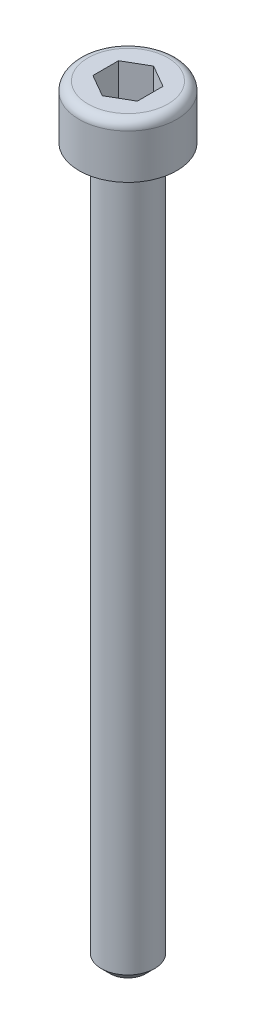
SolidWorks part; units mm, degrees
material "acero"
ref_plane "Alzado" through (0, 0, 0) normal (0, 0, 1) x (1, 0, 0)
ref_plane "Planta" through (0, 0, 0) normal (0, 1, 0) x (1, 0, 0)
ref_plane "Vista lateral" through (0, 0, 0) normal (1, 0, 0) x (0, 0, -1)
sketch "Croquis1" plane through (0, 0, 0) normal (0, 0, 1) x (1, 0, 0)
  line L0 (0, 0) -> (0, -60.9498) construction
  line L1 (0, 0) -> (2.75, 0)
  line L2 (2.75, 0) -> (2.75, -3)
  line L3 (2.75, -3) -> (1.5, -3)
  line L4 (1.5, -3) -> (1.5, -43)
  line L5 (1.5, -43) -> (0, -43)
  line L6 (0, -43) -> (0, 0)
  dimension "D1" = 40
  dimension "D2" = 3
  dimension "D3" = 5.5
  dimension "D4" = 3
revolve "Revolución1" add sketch "Croquis1" angle 360 about L0
sketch "Croquis2" plane through (0, 0, 0) normal (0, 1, 0) x (1, 0, 0)
  line L1 (1.25, 0.7217) -> (0, 1.4434)
  line L2 (0, 1.4434) -> (-1.25, 0.7217)
  line L3 (-1.25, 0.7217) -> (-1.25, -0.7217)
  line L4 (-1.25, -0.7217) -> (0, -1.4434)
  line L5 (0, -1.4434) -> (1.25, -0.7217)
  line L6 (1.25, -0.7217) -> (1.25, 0.7217)
  circle A0 centre (0, 0) radius 1.25 construction
  dimension "D1" = 2.5
extrude "Cortar-Extruir1" cut sketch "Croquis2" against normal blind 2
chamfer "Chaflán1" distance 0.5 angle 45 1 edges at (0, -43, 1.5)
fillet "Redondeo1" radius 0.5 1 edges at (0, 0, 2.75)
